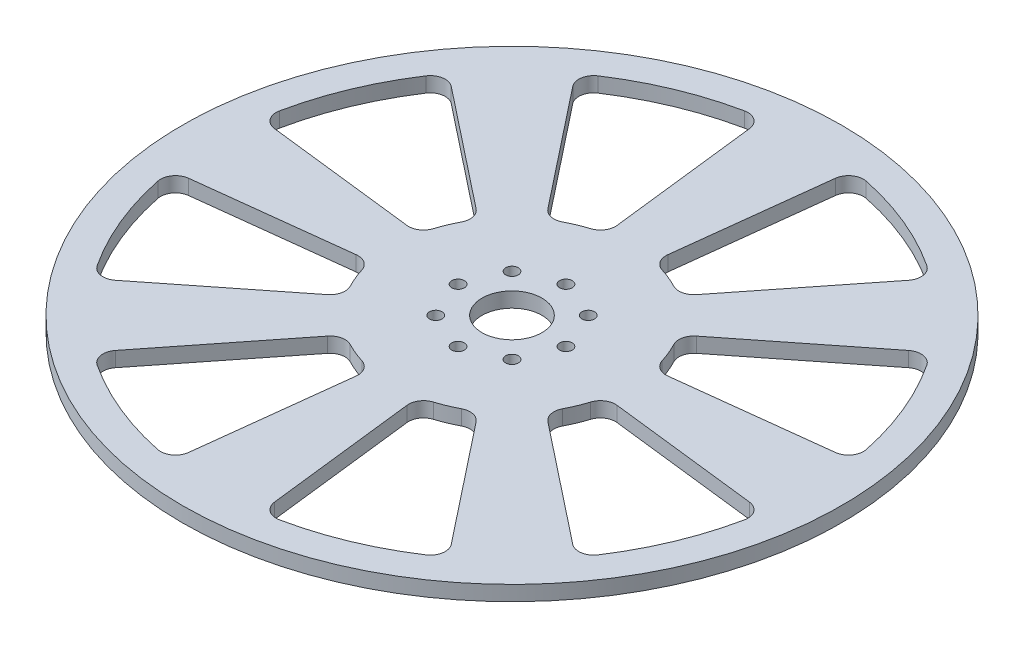
SolidWorks part; units mm, degrees
ref_plane "Спереди" through (0, 0, 0) normal (0, 0, 1) x (1, 0, 0)
ref_plane "Сверху" through (0, 0, 0) normal (0, 1, 0) x (1, 0, 0)
ref_plane "Справа" through (0, 0, 0) normal (1, 0, 0) x (0, 0, -1)
sketch "Эскиз1" plane through (0, 0, 0) normal (0, 1, 0) x (1, 0, 0)
  line L40 (-14.9578, -98.875) -> (-7.9599, -39.2)
  line L41 (14.9578, -98.875) -> (7.9599, -39.2)
  line L42 (80.4919, -59.3385) -> (33.3471, -22.0901)
  line L43 (22.0901, -33.3471) -> (59.3385, -80.4919)
  line L44 (98.875, -14.9578) -> (39.2, -7.9599)
  line L45 (39.2, 7.9599) -> (98.875, 14.9578)
  line L46 (33.3471, 22.0901) -> (80.4919, 59.3385)
  line L47 (22.0901, 33.3471) -> (59.3385, 80.4919)
  line L48 (7.9599, 39.2) -> (14.9578, 98.875)
  line L49 (-7.9599, 39.2) -> (-14.9578, 98.875)
  line L50 (-22.0901, 33.3471) -> (-59.3385, 80.4919)
  line L51 (-33.3471, 22.0901) -> (-80.4919, 59.3385)
  line L52 (-39.2, 7.9599) -> (-98.875, 14.9578)
  line L53 (-98.875, -14.9578) -> (-39.2, -7.9599)
  line L54 (-33.3471, -22.0901) -> (-80.4919, -59.3385)
  line L55 (-59.3385, -80.4919) -> (-22.0901, -33.3471)
  circle A0 centre (0, 0) radius 40
  circle A1 centre (0, 0) radius 10
  circle A2 centre (0, 0) radius 110
  circle A3 centre (0, 0) radius 100
  circle A13 centre (0, 0) radius 25
  circle A15 centre (0, 18) radius 2.1
  circle A16 centre (12.7279, -12.7279) radius 2.1
  circle A17 centre (-18, 0) radius 2.1
  circle A18 centre (0, -18) radius 2.1
  circle A19 centre (-12.7279, -12.7279) radius 2.1
  circle A20 centre (18, 0) radius 2.1
  circle A21 centre (12.7279, 12.7279) radius 2.1
  circle A22 centre (-12.7279, 12.7279) radius 2.1
extrude "Бобышка-Вытянуть3" add sketch "Эскиз1" along normal blind 5 contours A2 A3 | L52 A3 L53 A0 | L50 A3 L51 A0 | L48 A3 L49 A0 | L46 A3 L47 A0 | L44 A3 L45 A0 | L43 A3 L42 A0 | L40 A3 L41 A0 | L54 A3 L55 A0 | A0 A13 | A13 A22 A21 A20 A19 A18 A17 A16 A15 A1
fillet "Скругление2" radius 5 32 edges at (-39.2, 2.5, 7.9599) (-33.3471, 2.5, 22.0901) (-80.4919, 2.5, 59.3385) (-98.875, 2.5, 14.9578) (-14.9578, 2.5, 98.875) (-7.9599, 2.5, 39.2) (-22.0901, 2.5, 33.3471) (-59.3385, 2.5, 80.4919) (7.9599, 2.5, 39.2) (14.9578, 2.5, 98.875) (59.3385, 2.5, 80.4919) (22.0901, 2.5, 33.3471) (33.3471, 2.5, 22.0901) (80.4919, 2.5, 59.3385) (98.875, 2.5, 14.9578) (39.2, 2.5, 7.9599) (98.875, 2.5, -14.9578) (80.4919, 2.5, -59.3385) (33.3471, 2.5, -22.0901) (39.2, 2.5, -7.9599) (59.3385, 2.5, -80.4919) (14.9578, 2.5, -98.875) (7.9599, 2.5, -39.2) (22.0901, 2.5, -33.3471) (-7.9599, 2.5, -39.2) (-22.0901, 2.5, -33.3471) (-59.3385, 2.5, -80.4919) (-14.9578, 2.5, -98.875) (-98.875, 2.5, -14.9578) (-39.2, 2.5, -7.9599) (-33.3471, 2.5, -22.0901) (-80.4919, 2.5, -59.3385)
sketch3d "Трехмерный эскиз1"
  point P0 (9.607, 5, 24.5006)
sketch3d "Трехмерный эскиз2"
  point P0 (-10.5704, 5, -24.5175)
ref_plane "Плоскость2" through (0, 5, 0) normal (0, 1, 0) x (1, 0, 0)
sketch "Эскиз2" plane through (0, 5, 0) normal (0, 1, 0) x (1, 0, 0)
  circle A0 centre (0, 0) radius 25
  circle A1 centre (0, 0) radius 10
  circle A2 centre (-12.7279, 12.7279) radius 2.1
  circle A4 centre (12.7279, 12.7279) radius 2.1
  circle A7 centre (0, 18) radius 2.1
  circle A8 centre (18, 0) radius 2.1
  circle A9 centre (-18, 0) radius 2.1
  circle A10 centre (-12.7279, -12.7279) radius 2.1
  circle A11 centre (0, -18) radius 2.1
  circle A12 centre (12.7279, -12.7279) radius 2.1
